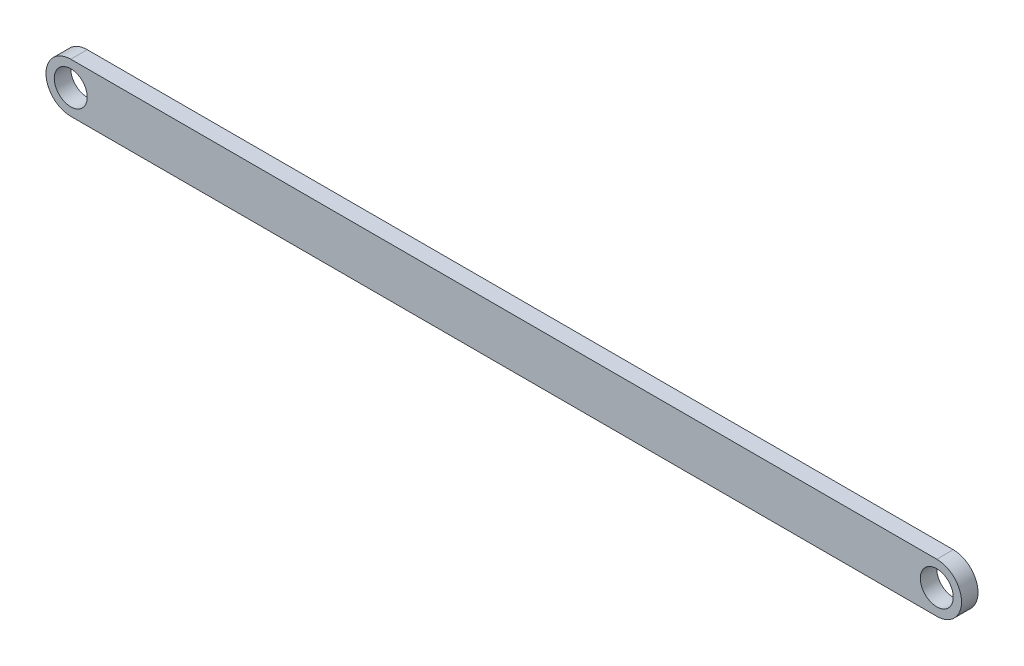
SolidWorks part; units mm, degrees
ref_plane "Спереди" through (0, 0, 0) normal (0, 0, 1) x (1, 0, 0)
ref_plane "Сверху" through (0, 0, 0) normal (0, 1, 0) x (1, 0, 0)
ref_plane "Справа" through (0, 0, 0) normal (1, 0, 0) x (0, 0, -1)
sketch "Эскиз1" plane through (0, 0, 0) normal (0, 0, 1) x (1, 0, 0)
  line L0 (0, 0) -> (-525, 0)
  line L1 (0, 30) -> (-525, 30)
  arc A0 (0, 0) -> (0, 30) centre (0, 15) ccw
  arc A1 (-525, 30) -> (-525, 0) centre (-525, 15) ccw
  dimension "D1" = 525
  dimension "D2" = 30
extrude "Бобышка-Вытянуть2" add sketch "Эскиз1" along normal blind 10 contours A1 L0 A0 L1
sketch "Эскиз2" plane through (0, 0, 0) normal (0, 0, -1) x (-1, 0, 0)
  circle A0 centre (0, 15) radius 10
  circle A1 centre (525, 15) radius 10
  dimension "D1" = 20
  dimension "D2" = 20
extrude "Вырез-Вытянуть1" cut sketch "Эскиз2" against normal blind 10
